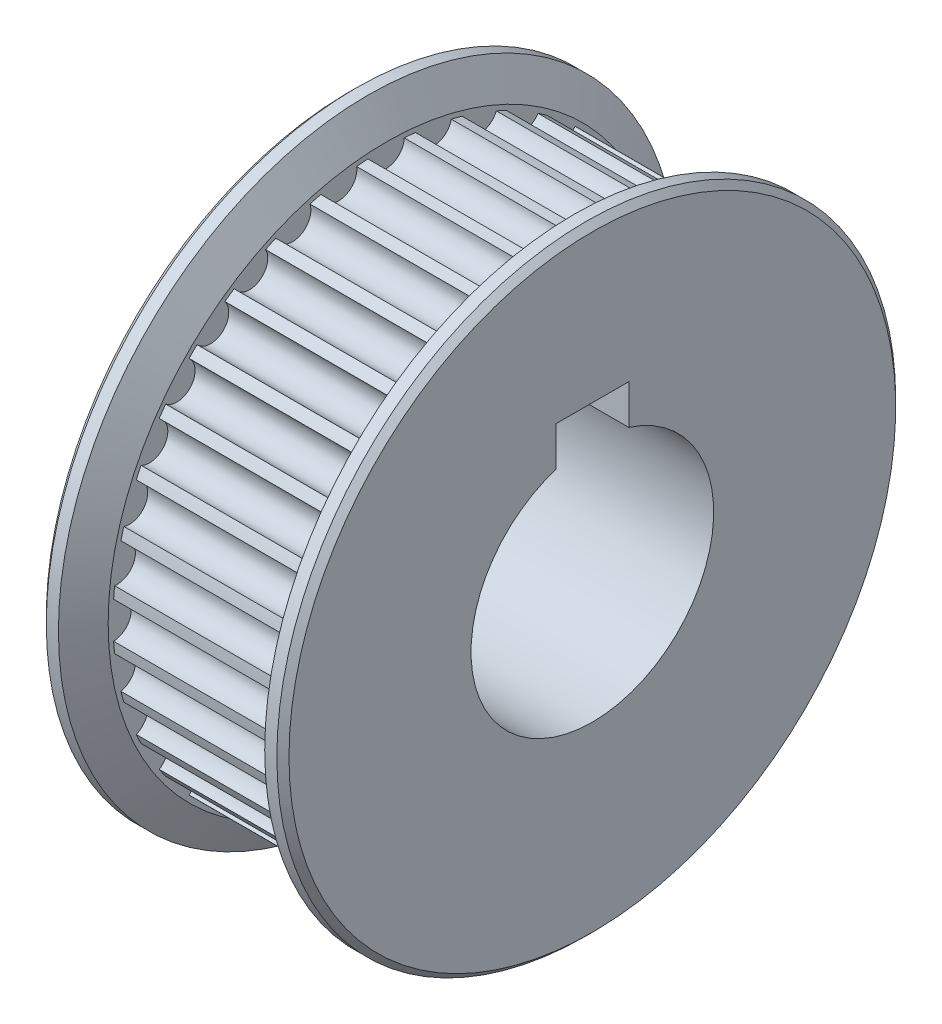
SolidWorks part; units mm, degrees
material "Lega 6061"
ref_plane "Piano frontale" through (0, 0, 0) normal (0, 0, 1) x (1, 0, 0)
ref_plane "Piano superiore" through (0, 0, 0) normal (0, 1, 0) x (1, 0, 0)
ref_plane "Piano destro" through (0, 0, 0) normal (1, 0, 0) x (0, 0, -1)
sketch "Schizzo4" plane through (0, 0, 0) normal (0, 0, 1) x (1, 0, 0)
  line L0 (0, 0) -> (25.6817, 0) construction
  line L1 (0, 2.5) -> (0, 8)
  line L2 (0, 8) -> (7, 8)
  line L3 (7, 8) -> (7, 12.75)
  line L4 (7, 12.75) -> (7.75, 12.75)
  line L5 (7.75, 12.75) -> (8.5, 11.451)
  line L6 (8.5, 11.451) -> (8.5, 11.25)
  line L7 (8.5, 11.25) -> (15.5, 11.25)
  line L8 (15.5, 11.25) -> (15.5, 11.451)
  line L9 (15.5, 11.451) -> (16.25, 12.75)
  line L10 (16.25, 12.75) -> (17, 12.75)
  line L11 (17, 12.75) -> (17, 2.5)
  line L12 (17, 2.5) -> (0, 2.5)
  line L13 (12, 11.25) -> (12, 0) construction
  dimension "D1" = 7
  dimension "D2" = 5
  dimension "D3" = 17
  dimension "D4" = 5
  dimension "D5" = 16
  dimension "D6" = 25.5
  dimension "D7" = 22.5
  dimension "D8" = 1.5
  dimension "D9" = 0.75
  dimension "D10" = 60
revolve "Rivoluzione1" add sketch "Schizzo4" angle 360 about L0
sketch "Schizzo5" plane through (8.5, 0, 0) normal (1, 0, 0) x (0, 0, -1)
  circle A0 centre (0, 11.25) radius 0.75
  circle A1 centre (0, 0) radius 11.25 construction
  circle A29 centre (1.9535, 11.0791) radius 0.75
  circle A30 centre (3.8477, 10.5715) radius 0.75
  circle A31 centre (5.625, 9.7428) radius 0.75
  circle A32 centre (7.2314, 8.618) radius 0.75
  circle A33 centre (8.618, 7.2314) radius 0.75
  circle A34 centre (9.7428, 5.625) radius 0.75
  circle A35 centre (10.5715, 3.8477) radius 0.75
  circle A36 centre (11.0791, 1.9535) radius 0.75
  circle A37 centre (11.25, 0) radius 0.75
  circle A38 centre (11.0791, -1.9535) radius 0.75
  circle A39 centre (10.5715, -3.8477) radius 0.75
  circle A40 centre (9.7428, -5.625) radius 0.75
  circle A41 centre (8.618, -7.2314) radius 0.75
  circle A42 centre (7.2314, -8.618) radius 0.75
  circle A43 centre (5.625, -9.7428) radius 0.75
  circle A44 centre (3.8477, -10.5715) radius 0.75
  circle A45 centre (1.9535, -11.0791) radius 0.75
  circle A46 centre (0, -11.25) radius 0.75
  circle A47 centre (-1.9535, -11.0791) radius 0.75
  circle A48 centre (-3.8477, -10.5715) radius 0.75
  circle A49 centre (-5.625, -9.7428) radius 0.75
  circle A50 centre (-7.2314, -8.618) radius 0.75
  circle A51 centre (-8.618, -7.2314) radius 0.75
  circle A52 centre (-9.7428, -5.625) radius 0.75
  circle A53 centre (-10.5715, -3.8477) radius 0.75
  circle A54 centre (-11.0791, -1.9535) radius 0.75
  circle A55 centre (-11.25, 0) radius 0.75
  circle A56 centre (-11.0791, 1.9535) radius 0.75
  circle A57 centre (-10.5715, 3.8477) radius 0.75
  circle A58 centre (-9.7428, 5.625) radius 0.75
  circle A59 centre (-8.618, 7.2314) radius 0.75
  circle A60 centre (-7.2314, 8.618) radius 0.75
  circle A61 centre (-5.625, 9.7428) radius 0.75
  circle A62 centre (-3.8477, 10.5715) radius 0.75
  circle A63 centre (-1.9535, 11.0791) radius 0.75
  point P78 (0, 0)
  dimension "D1" = 1.5
  dimension "D2" = 36
extrude "Taglio-Estrusione1" cut sketch "Schizzo5" against normal up to surface (7 mm away)
sketch "Schizzo6" plane through (0, 0, 0) normal (0, 0, 1) x (1, 0, 0)
  line L0 (0, 0) -> (23.7398, 0) construction
  line L1 (3.5, 8) -> (3.5, -8) construction
  line L2 (7, 8) -> (0, 8) construction
  line L3 (0, -8) -> (7, -8) construction
  circle A0 centre (3.5, 0) radius 1.5
  dimension "D1" = 3
extrude "Taglio-Estrusione2" cut sketch "Schizzo6" along normal up to surface (8 mm away) up to face at (0, 0, 8)
cosmetic thread "Filettatura cosmetica2" parameters "D2"=4
sketch "Schizzo7" plane through (0, 0, 0) normal (0, 1, 0) x (1, 0, 0)
  line L0 (3.5, 8) -> (3.5, -7.8581) construction
  line L1 (7, 8) -> (0, 8) construction
  circle A0 centre (3.5, 0) radius 1.5
  spline S0 degree 2 poles (2, -8) (3.5, -7.7188) (5, -8) knots 0 0 0 1 1 1 weights 0.0065 0.008 0.0095 construction
  dimension "D1" = 3
extrude "Taglio-Estrusione3" cut sketch "Schizzo7" along normal up to surface (7.8581 mm away)
cosmetic thread "Filettatura cosmetica1" parameters "D2"=4
chamfer "Smusso1" distance 0.5 angle 45 2 edges at (0, 0, 8) (0, 0, 2.5)
chamfer "Smusso2" distance 0.25 angle 45 2 edges at (17, 0, 12.75) (7, 0, 12.75)
sketch "Schizzo8" plane through (0, 0, 0) normal (-1, 0, 0) x (0, 0, 1)
  circle A0 centre (0, 0) radius 5
  dimension "D1" = 10
extrude "Taglio-Estrusione4" cut sketch "Schizzo8" against normal through all
sketch "Schizzo9" plane through (0, 0, 0) normal (-1, 0, 0) x (0, 0, 1)
  circle A0 centre (0, 0) radius 8
extrude "Taglio-Estrusione5" cut sketch "Schizzo9" against normal blind 7
ref_plane "Piano1" through (15.5, 3.1348, -10.8044) normal (-1, 0, 0) x (0, 0, 1)
sketch "Schizzo10" plane through (15.5, 3.1348, -10.8044) normal (-1, 0, 0) x (0, 0, 1)
  line L0 (10.8044, -3.1348) -> (10.8044, 9.6652) construction
  line L1 (9.3044, 3.2652) -> (12.3044, 3.2652)
  line L2 (9.3044, 3.2652) -> (9.3044, 1.6349)
  line L3 (9.3044, 1.6349) -> (12.3044, 1.6349)
  line L4 (12.3044, 1.6349) -> (12.3044, 3.2652)
  circle A0 centre (10.8044, -3.1348) radius 5 construction
  point P3 (10.8044, 1.8652)
  point P6 (10.8044, 3.2652)
  dimension "D1" = 3
  dimension "D2" = 1.4
extrude "Taglio-Estrusione6" cut sketch "Schizzo10" along normal through all and the other way blind 7
